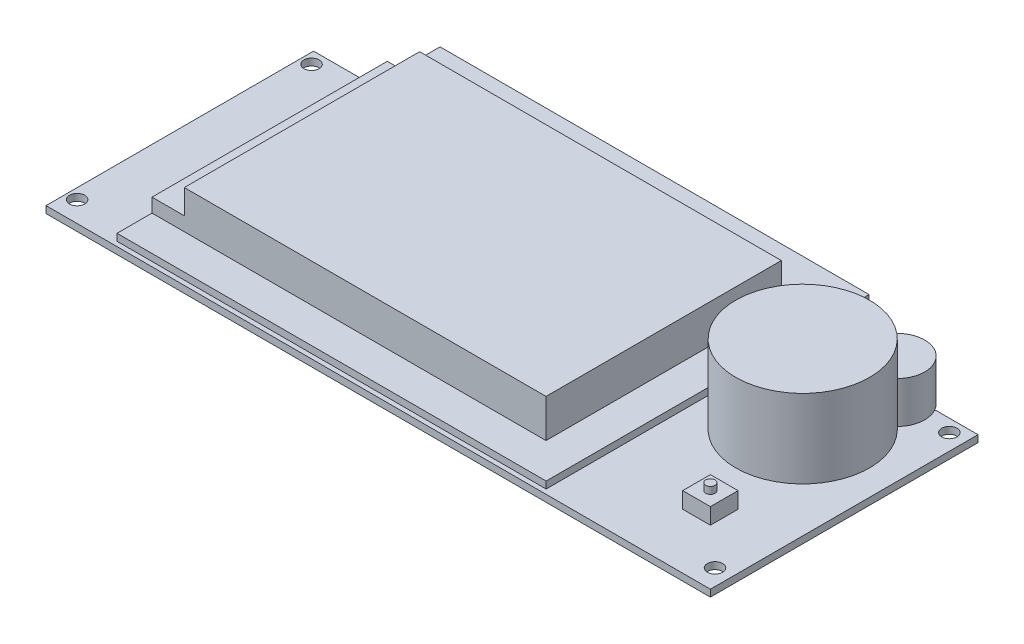
SolidWorks part; units mm, degrees
ref_plane "Front Plane" through (0, 0, 0) normal (0, 0, 1) x (1, 0, 0)
ref_plane "Top Plane" through (0, 0, 0) normal (0, 1, 0) x (1, 0, 0)
ref_plane "Right Plane" through (0, 0, 0) normal (1, 0, 0) x (0, 0, -1)
sketch "Sketch1" plane through (0, 0, 0) normal (0, 1, 0) x (1, 0, 0)
  line L1 (-72, -29) -> (72, -29)
  line L2 (-72, -29) -> (-72, 29)
  line L3 (-72, 29) -> (72, 29)
  line L4 (72, -29) -> (72, 29)
  line L5 (-72, -29) -> (72, 29) construction
  line L6 (-72, 29) -> (72, -29) construction
  point P0 (0, 0)
  dimension "D1" = 144
  dimension "D2" = 58
extrude "Boss-Extrude2" add sketch "Sketch1" along normal blind 1.5
sketch "Sketch2" plane through (0, 1.5, 0) normal (0, 1, 0) x (1, 0, 0)
  line L0 (-57.6, -28) -> (35.4, -28)
  line L1 (35.4, -28) -> (35.4, 42)
  line L2 (-72, -29) -> (72, -29) construction
  line L3 (-72, 29) -> (-72, -29) construction
  line L4 (35.4, 42) -> (-57.6, 42)
  line L5 (-57.6, 42) -> (-57.6, -28)
  dimension "D1" = 1
  dimension "D2" = 14.4
  dimension "D3" = 93
  dimension "D4" = 70
extrude "Boss-Extrude3" add sketch "Sketch2" along normal blind 1.5
sketch "Sketch3" plane through (0, 3, 0) normal (0, 1, 0) x (1, 0, 0)
  line L0 (-50.6, -20.4239) -> (27.8, -20.4239)
  line L1 (27.8, -20.4239) -> (27.8, 30.5761)
  line L2 (-57.6, 42) -> (-57.6, -28) construction
  line L3 (27.8, 30.5761) -> (-50.6, 30.5761)
  line L4 (-50.6, 30.5761) -> (-50.6, -20.4239)
  dimension "D1" = 7
  dimension "D2" = 78.4
  dimension "D3" = 51
extrude "Boss-Extrude4" add sketch "Sketch3" along normal blind 8.3
sketch "Sketch4" plane through (0, 3, 0) normal (0, 1, 0) x (1, 0, 0)
  line L0 (-50.6, 30.5761) -> (-57.6, 30.5761)
  line L1 (-57.6, 42) -> (-57.6, -28) construction
  line L2 (-57.6, 30.5761) -> (-57.6, -20.4239)
  line L3 (-57.6, 29) -> (-57.6, -28) construction
  line L4 (-57.6, -20.4239) -> (-50.6, -20.4239)
  line L5 (-50.6, -20.4239) -> (-50.6, 30.5761)
extrude "Boss-Extrude5" add sketch "Sketch4" along normal blind 3
sketch "Sketch5" plane through (0, 1.5, 0) normal (0, 1, 0) x (1, 0, 0)
  line L0 (72, 29) -> (35.4, 29) construction
  line L1 (52, 10) -> (66, 10) construction
  line L2 (52, 10) -> (52, -2) construction
  line L3 (52, -2) -> (66, -2) construction
  line L4 (66, 10) -> (66, -2) construction
  line L5 (52, 10) -> (66, -2) construction
  line L6 (52, -2) -> (66, 10) construction
  line L7 (72, -29) -> (72, 29) construction
  circle A0 centre (59, 4) radius 3.5
  point P0 (59, 4)
  dimension "D5" = 7
  dimension "D1" = 31
  dimension "D2" = 12
  dimension "D3" = 14
  dimension "D4" = 6
extrude "Boss-Extrude6" add sketch "Sketch5" along normal blind 7
sketch "Sketch6" plane through (0, 8.5, 0) normal (0, 1, 0) x (1, 0, 0)
  circle A0 centre (59, 4) radius 14.5
  dimension "D1" = 29
extrude "Boss-Extrude7" add sketch "Sketch6" along normal blind 17
sketch "Sketch8" plane through (0, 1.5, 0) normal (0, 1, 0) x (1, 0, 0)
  line L0 (72, -29) -> (72, 29) construction
  line L1 (72, 29) -> (35.4, 29) construction
  circle A0 centre (57.45, 26) radius 6
  dimension "D1" = 12
  dimension "D2" = 14.55
  dimension "D3" = 3
extrude "Boss-Extrude8" add sketch "Sketch8" along normal blind 9
sketch "Sketch9" plane through (0, 1.5, 0) normal (0, 1, 0) x (1, 0, 0)
  line L0 (72, -29) -> (72, 29) construction
  line L1 (54, -11) -> (60, -11)
  line L2 (54, -11) -> (54, -17)
  line L3 (54, -17) -> (60, -17)
  line L4 (60, -11) -> (60, -17)
  line L5 (54, -11) -> (60, -17) construction
  line L6 (54, -17) -> (60, -11) construction
  line L7 (-72, -29) -> (72, -29) construction
  point P0 (57, -14)
  point P5 (54, -14)
  dimension "D1" = 6
  dimension "D2" = 6
  dimension "D3" = 18
  dimension "D4" = 18
extrude "Boss-Extrude9" add sketch "Sketch9" along normal blind 3.5
sketch "Sketch10" plane through (0, 5, 0) normal (0, 1, 0) x (1, 0, 0)
  circle A0 centre (57, -14) radius 1.0169
extrude "Boss-Extrude10" add sketch "Sketch10" along normal blind 1.5
sketch "Sketch11" plane through (0, 0, 0) normal (0, -1, 0) x (1, 0, 0)
  line L0 (72, -29) -> (-72, -29) construction
  line L1 (-4, -6.5) -> (16, -6.5)
  line L2 (-4, -6.5) -> (-4, 2.5)
  line L3 (-4, 2.5) -> (16, 2.5)
  line L4 (16, -6.5) -> (16, 2.5)
  line L5 (-4, -6.5) -> (16, 2.5) construction
  line L6 (-4, 2.5) -> (16, -6.5) construction
  line L7 (72, 29) -> (72, -29) construction
  line L8 (-72, -29) -> (-72, 29) construction
  line L9 (-25.8, -6.5) -> (-5.8, -6.5)
  line L10 (-25.8, -6.5) -> (-25.8, 2.5)
  line L11 (-25.8, 2.5) -> (-5.8, 2.5)
  line L12 (-5.8, -6.5) -> (-5.8, 2.5)
  line L13 (-25.8, -6.5) -> (-5.8, 2.5) construction
  line L14 (-25.8, 2.5) -> (-5.8, -6.5) construction
  point P0 (6, -2)
  point P9 (-15.8, -2)
  dimension "D1" = 9
  dimension "D2" = 20
  dimension "D3" = 31.5
  dimension "D4" = 76
  dimension "D5" = 9
  dimension "D6" = 20
  dimension "D7" = 66.2
  dimension "D8" = 22.5
extrude "Boss-Extrude11" add sketch "Sketch11" along normal blind 9
sketch "Sketch12" plane through (0, 0, 0) normal (0, 1, 0) x (1, 0, 0)
  line L0 (72, -29) -> (72, 29) construction
  line L1 (72, 29) -> (62.6462, 29) construction
  line L2 (-72, -29) -> (72, -29) construction
  line L3 (-72, 29) -> (-72, -29) construction
  line L4 (-57.6, 29) -> (-72, 29) construction
  circle A0 centre (68.5, 26.3) radius 1.65
  circle A1 centre (68.5, -24.5) radius 1.65
  circle A2 centre (-69.75, 26.3) radius 1.65
  circle A3 centre (-69.75, -24.5) radius 1.65
  dimension "D1" = 3.3
  dimension "D6" = 3.3
  dimension "D8" = 3.3
  dimension "D12" = 3.3
  dimension "D2" = 3.5
  dimension "D3" = 2.7
  dimension "D4" = 3.5
  dimension "D5" = 4.5
  dimension "D7" = 2.25
  dimension "D9" = 2.7
  dimension "D10" = 4.5
  dimension "D11" = 2.25
extrude "Cut-Extrude2" cut sketch "Sketch12" along normal blind 10
